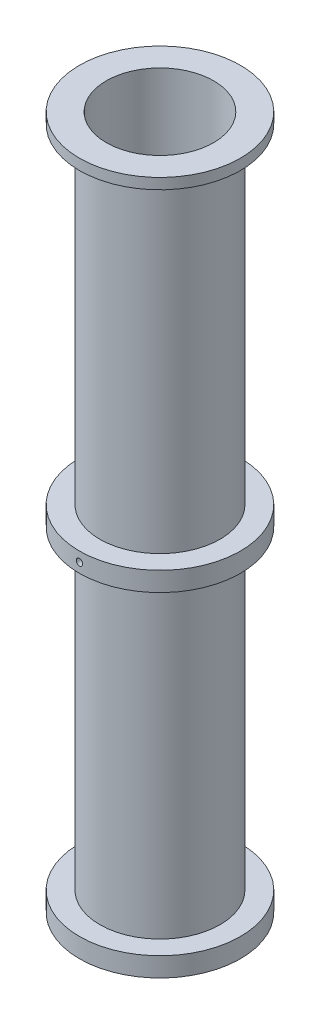
SolidWorks part; units mm, degrees
ref_plane "Front Plane" through (0, 0, 0) normal (0, 0, 1) x (1, 0, 0)
ref_plane "Top Plane" through (0, 0, 0) normal (0, 1, 0) x (1, 0, 0)
ref_plane "Right Plane" through (0, 0, 0) normal (1, 0, 0) x (0, 0, -1)
sketch "Sketch1" plane through (0, 0, 0) normal (1, 0, 0) x (0, 0, -1)
  line L0 (0, 0) -> (-37.5, 0)
  line L1 (-37.5, 0) -> (-37.5, 9)
  line L2 (-37.5, 9) -> (-28, 9)
  line L3 (-28, 9) -> (-28, 155.5)
  line L4 (-37.5, 323) -> (-25, 323)
  line L5 (-25, 323) -> (-25, 3)
  line L6 (-25, 3) -> (0, 3)
  line L7 (0, 3) -> (0, 0)
  line L9 (-37.5, 323) -> (-37.5, 318)
  line L10 (-37.5, 318) -> (-28, 318)
  line L11 (-28, 164.5) -> (-37.5, 164.5)
  line L12 (-37.5, 164.5) -> (-37.5, 155.5)
  line L13 (-37.5, 155.5) -> (-28, 155.5)
  line L14 (-28, 164.5) -> (-28, 318)
  line L15 (-28, 155.5) -> (-28, 164.5) construction
  point P3 (-28, 160)
  point P17 (-28, 164.5)
  point P18 (-28, 155.5)
  point P21 (-28, 160)
  dimension "D1" = 37.5
  dimension "D2" = 9
  dimension "D4" = 3
  dimension "D5" = 3
  dimension "D6" = 5
  dimension "D7" = 320
  dimension "D3" = 25
  dimension "D8" = 160
  dimension "D9" = 9
revolve "Revolve1" add sketch "Sketch1" angle 360 about L7
ref_plane "Plane1" through (0, 0, -37.5) normal (0, 0, -1) x (-1, 0, 0)
sketch "Sketch2" plane through (0, 0, -37.5) normal (0, 0, -1) x (-1, 0, 0)
  line L0 (-37.5, 164.5) -> (-37.5, 155.5) construction
  line L2 (37.5, 164.5) -> (-37.5, 164.5) construction
  line L3 (-37.5, 164.5) -> (-37.5, 155.5) construction
  line L4 (37.5, 155.5) -> (37.5, 164.5) construction
  line L5 (37.5, 155.5) -> (37.5, 164.5) construction
  line L6 (-37.5, 155.5) -> (37.5, 155.5) construction
  line L7 (-37.5, 155.5) -> (37.5, 155.5) construction
  line L8 (0, 164.5) -> (0, 155.5) construction
  circle A0 centre (0, 160) radius 1.5
  dimension "D2" = 3
extrude "Cut-Extrude1" cut sketch "Sketch2" against normal up to next
pattern_circular "CirPattern1" count 2 over 360 about axis through (0, 160, 0) along (0, 0, 1) of "Cut-Extrude1"
equation "\"ABS_Thickness\"=3"
equation "\"Cavity_Length\"= 320"
equation "\"D8@Sketch1\"=\"Cavity_Length\"*0.5"
equation "\"thick_flange\"=9"
equation "\"Cavity_radius_internal\"=25"
equation "\"AirHole_Diameter\"=3"
equation "\"AirHole_Number\"=2"
equation "\"Rocket_Radius_Internal\"=37.5"
